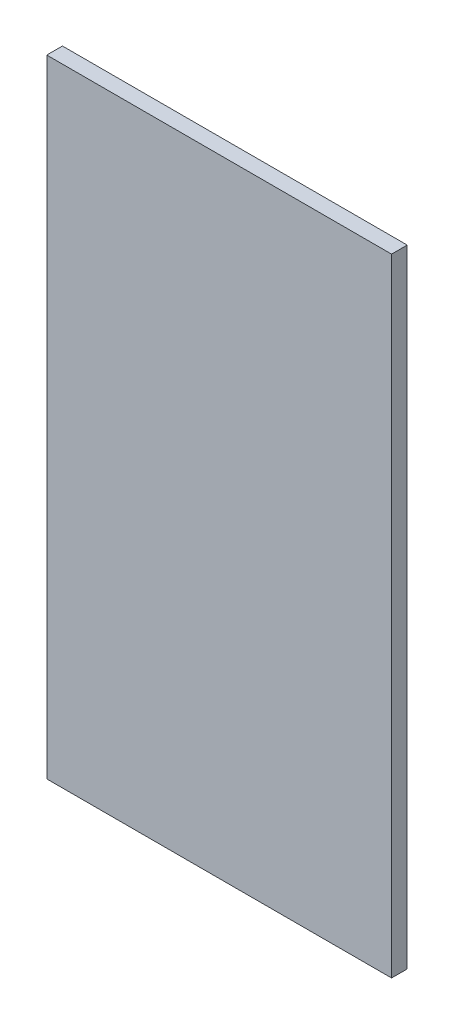
SolidWorks part; units mm, degrees
ref_plane "Front Plane" through (0, 0, 0) normal (0, 0, 1) x (1, 0, 0)
ref_plane "Top Plane" through (0, 0, 0) normal (0, 1, 0) x (1, 0, 0)
ref_plane "Right Plane" through (0, 0, 0) normal (1, 0, 0) x (0, 0, -1)
sketch "Sketch1" plane through (0, 0, 0) normal (0, 0, 1) x (1, 0, 0)
  line L0 (314.325, 215.9) -> (314.325, 241.3) construction
  line L1 (314.325, 241.3) -> (390.525, 241.3) construction
  line L2 (390.525, 241.3) -> (390.525, 215.9) construction
  line L3 (390.525, 215.9) -> (314.325, 215.9) construction
  line L4 (454.025, -12.7) -> (428.625, -12.7) construction
  line L5 (428.625, -12.7) -> (428.625, 12.7) construction
  line L6 (428.625, 12.7) -> (454.025, 12.7) construction
  line L7 (454.025, 12.7) -> (454.025, -12.7) construction
  line L8 (314.325, 215.9) -> (314.325, 241.3) construction
  line L9 (314.325, 241.3) -> (390.525, 241.3) construction
  line L10 (390.525, 241.3) -> (390.525, 215.9) construction
  line L11 (390.525, 215.9) -> (314.325, 215.9) construction
  line L12 (454.025, -12.7) -> (428.625, -12.7) construction
  line L13 (428.625, -12.7) -> (428.625, 12.7) construction
  line L14 (428.625, 12.7) -> (454.025, 12.7) construction
  line L15 (454.025, 12.7) -> (454.025, -12.7) construction
  line L17 (454.025, -12.7) -> (314.325, -12.7)
  line L18 (454.025, -12.7) -> (454.025, 241.3)
  line L19 (454.025, 241.3) -> (314.325, 241.3)
  line L20 (314.325, -12.7) -> (314.325, 241.3)
extrude "Boss-Extrude1" add sketch "Sketch1" along normal blind 6.35
